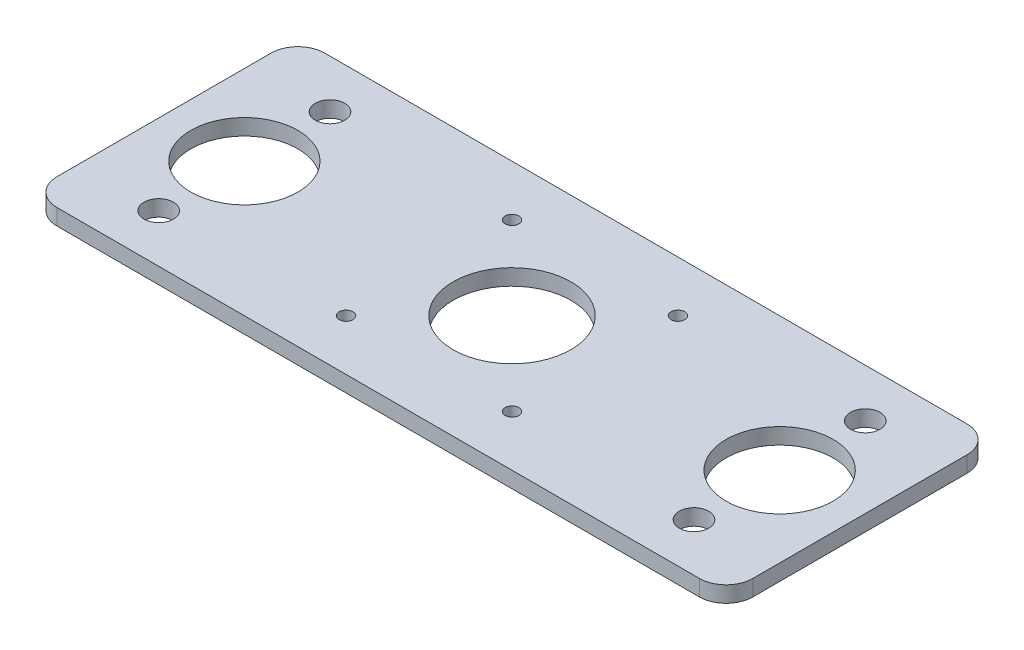
SolidWorks part; units mm, degrees
ref_plane "前视基准面" through (0, 0, 0) normal (0, 0, 1) x (1, 0, 0)
ref_plane "上视基准面" through (0, 0, 0) normal (0, 1, 0) x (1, 0, 0)
ref_plane "右视基准面" through (0, 0, 0) normal (1, 0, 0) x (0, 0, -1)
sketch "草图1" plane through (0, 0, 0) normal (0, 1, 0) x (1, 0, 0)
  line L2 (0, 25) -> (60, 25)
  line L3 (65, 20) -> (65, -20)
  line L4 (60, -25) -> (-60, -25)
  line L5 (-65, -20) -> (-65, 20)
  line L6 (-60, 25) -> (0, 25)
  circle A0 centre (0, 0) radius 11
  circle A1 centre (0, 0) radius 4.5
  circle A2 centre (15.5, 15.5) radius 1.2836
  circle A3 centre (15.5, -15.5) radius 1.2836
  circle A4 centre (-15.5, -15.5) radius 1.2836
  circle A5 centre (-15.5, 15.5) radius 1.2836
  circle A6 centre (50, 0) radius 10
  circle A7 centre (50, 16) radius 2.75
  circle A8 centre (50, -16) radius 2.75
  circle A9 centre (-50, -16) radius 2.75
  circle A10 centre (-50, 16) radius 2.75
  circle A11 centre (-50, 0) radius 10
  arc A12 (-60, -25) -> (-65, -20) centre (-60, -20) cw
  arc A13 (60, -25) -> (65, -20) centre (60, -20) ccw
  arc A14 (65, 20) -> (60, 25) centre (60, 20) ccw
  arc A15 (-65, 20) -> (-60, 25) centre (-60, 20) cw
  point P16 (0, 0)
  dimension "D1" = 4
  dimension "D2" = 50
  dimension "D4" = 5
  dimension "D6" = 20
  dimension "D3" = 32
  dimension "D5" = 50
extrude "凸台-拉伸1" add sketch "草图1" along normal blind 3 contours A15 L5 A12 L4 A13 L3 A14 L2 L6 A10 A0 A2 A3 A4 A5 A6 A7 A8 A9 A11
